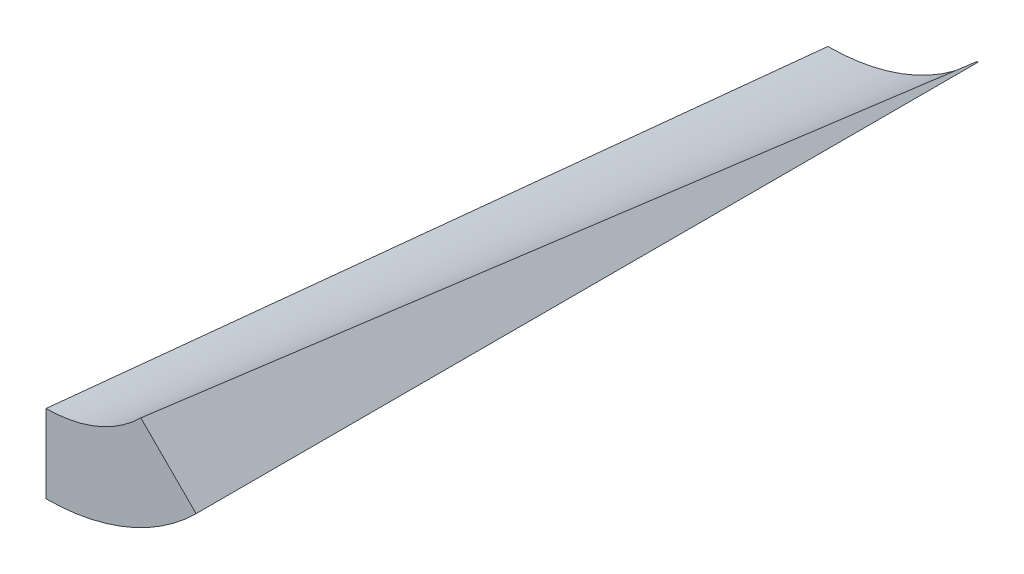
SolidWorks part; units mm, degrees
material "PLA"
ref_plane "Front Plane" through (0, 0, 0) normal (0, 0, 1) x (1, 0, 0)
ref_plane "Top Plane" through (0, 0, 0) normal (0, 1, 0) x (1, 0, 0)
ref_plane "Right Plane" through (0, 0, 0) normal (1, 0, 0) x (0, 0, -1)
sketch "Sketch1" plane through (0, 0, 0) normal (0, 0, 1) x (1, 0, 0)
  line L0 (0, 0) -> (0, 50000) construction
  line L1 (19.0919, 8.0581) -> (-35336.2472, 35363.3972) construction
  line L2 (0, 0.1) -> (0, 0)
  line L3 (19.1272, 8.0228) -> (19.1979, 7.9521)
  arc A0 (0, 0) -> (19.1979, 7.9521) centre (0, 27.15) ccw
  arc A1 (0, 0.1) -> (19.1272, 8.0228) centre (0, 27.15) ccw
  dimension "D1" = 27.15
  dimension "D2" = 45
  dimension "D3" = 0.1
ref_plane "Plane1" through (0, 0, 100) normal (0, 0, 1) x (1, 0, 0)
sketch "Sketch2" plane through (0, 0, 100) normal (0, 0, 1) x (1, 0, 0)
  line L3 (0, 10) -> (0, 0)
  line L4 (12.1269, 15.0231) -> (19.1979, 7.9521)
  arc A0 (0, 0) -> (19.1979, 7.9521) centre (0, 27.15) ccw
  arc A1 (0, 0) -> (19.1979, 7.9521) centre (0, 27.15) ccw construction
  arc A2 (0, 10) -> (12.1269, 15.0231) centre (0, 27.15) ccw
  dimension "D1" = 10
loft "Loft3" add profiles "Sketch1", "Sketch2"
equation "\"tube_id\"= 54.3mm"
equation "\"D1@Sketch1\"=\"tube_id\"/2"
